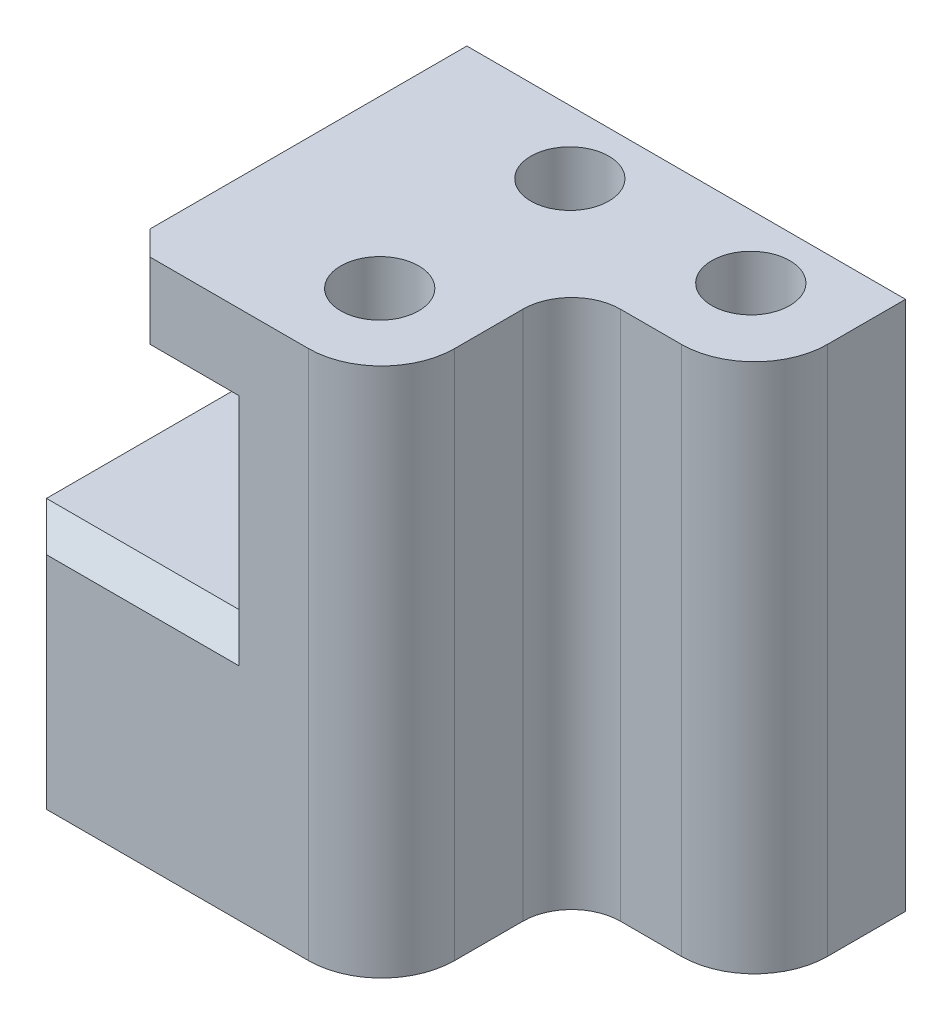
SolidWorks part; units mm, degrees
ref_plane "Plano frontal" through (0, 0, 0) normal (0, 0, 1) x (1, 0, 0)
ref_plane "Plano superior" through (0, 0, 0) normal (0, 1, 0) x (1, 0, 0)
ref_plane "Plano direito" through (0, 0, 0) normal (1, 0, 0) x (0, 0, -1)
sketch "Esboço1" plane through (0, 0, 0) normal (0, 0, 1) x (1, 0, 0)
  line L0 (0, 0) -> (0, 21.75)
  line L1 (0, 21.75) -> (-10.5, 21.75)
  line L2 (-10.5, 21.75) -> (-10.5, 17.65)
  line L3 (-10.5, 17.65) -> (-6.85, 17.65)
  line L4 (-6.85, 17.65) -> (-6.85, 10.05)
  line L5 (-6.85, 10.05) -> (-14.75, 10.05)
  line L6 (-14.75, 10.05) -> (-14.75, 0)
  line L7 (-14.75, 0) -> (0, 0)
  dimension "D1" = 10.05
  dimension "D2" = 7.6
  dimension "D3" = 14.75
  dimension "D4" = 6.85
  dimension "D5" = 4.1
  dimension "D6" = 10.5
extrude "Ressalto-extrusão1" add sketch "Esboço1" along normal blind 15
sketch "Esboço2" plane through (0, 21.75, 0) normal (0, 1, 0) x (1, 0, 0)
  line L1 (-7.35, -15) -> (-7.35, 0) construction
  line L2 (-7.35, -7.5) -> (0, -7.5) construction
  line L3 (0, -15) -> (0, 0) construction
  line L4 (-3.675, -11.4) -> (-3.675, -3.6) construction
  line L5 (-3.675, -2) -> (7.0515, -2) construction
  line L6 (0, 0) -> (-10.5, 0) construction
  line L7 (-6.85, -15) -> (-6.85, 0) construction
  line L8 (-0.4996, -11.4) -> (-2.0873, -8.65) construction
  line L9 (-2.0873, -8.65) -> (-5.2627, -8.65) construction
  line L10 (-5.2627, -8.65) -> (-6.8504, -11.4) construction
  line L11 (-6.8504, -11.4) -> (-5.2627, -14.15) construction
  line L12 (-5.2627, -14.15) -> (-2.0873, -14.15) construction
  line L13 (-2.0873, -14.15) -> (-0.4996, -11.4) construction
  line L14 (-6.85, -15) -> (-6.85, 0) construction
  circle A0 centre (-3.675, -3.6) radius 1.6
  circle A1 centre (-3.675, -11.4) radius 1.6
  circle A2 centre (-3.675, -11.4) radius 2.75 construction
  point P10 (-3.675, -7.5)
  point P12 (-3.675, -7.5)
  dimension "D1" = 3.2
  dimension "D2" = 2
  dimension "D3" = 5.5
  dimension "D4" = 0.5
extrude "Corte-extrusão1" cut sketch "Esboço2" against normal up to next
sketch "Esboço3" plane through (0, 21.75, 0) normal (0, 1, 0) x (1, 0, 0)
  line L0 (0, -15) -> (0, 0) construction
  line L1 (7.5, -7.2) -> (0, -7.2)
  line L2 (7.5, -7.2) -> (7.5, 0)
  line L3 (7.5, 0) -> (0, 0)
  line L4 (0, -7.2) -> (0, 0)
  line L5 (7.5, -7.2) -> (0, 0) construction
  line L6 (7.5, 0) -> (0, -7.2) construction
  line L7 (-3.675, -3.6) -> (3.75, -3.6) construction
  circle A0 centre (3.75, -3.6) radius 1.6
  point P0 (3.75, -3.6)
  dimension "D3" = 3.2
  dimension "D1" = 7.5
extrude "Ressalto-extrusão2" add sketch "Esboço3" against normal up to surface (21.75 mm away) up to face at (-3.675, 0, 5.2)
fillet "Filete1" radius 2 1 edges at (0, 10.875, 7.2)
fillet "Filete2" radius 3 2 edges at (7.5, 10.875, 7.2) (0, 10.875, 15)
chamfer "Chanfro1" distance 1 angle 45 8 edges at (7.5, 10.875, 0) (-1.5, 21.75, 0) (-10.5, 19.7, 0) (-8.675, 17.65, 0) (-6.85, 13.85, 0) (-10.8, 10.05, 0) (-14.75, 5.025, 0) (-3.625, 0, 0)
chamfer "Chanfro2" distance 1 angle 45 5 edges at (-14.75, 5.025, 15) (-10.5, 19.7, 15) (-10.8, 10.05, 15) (-6.85, 13.85, 15) (-8.675, 17.65, 15)
